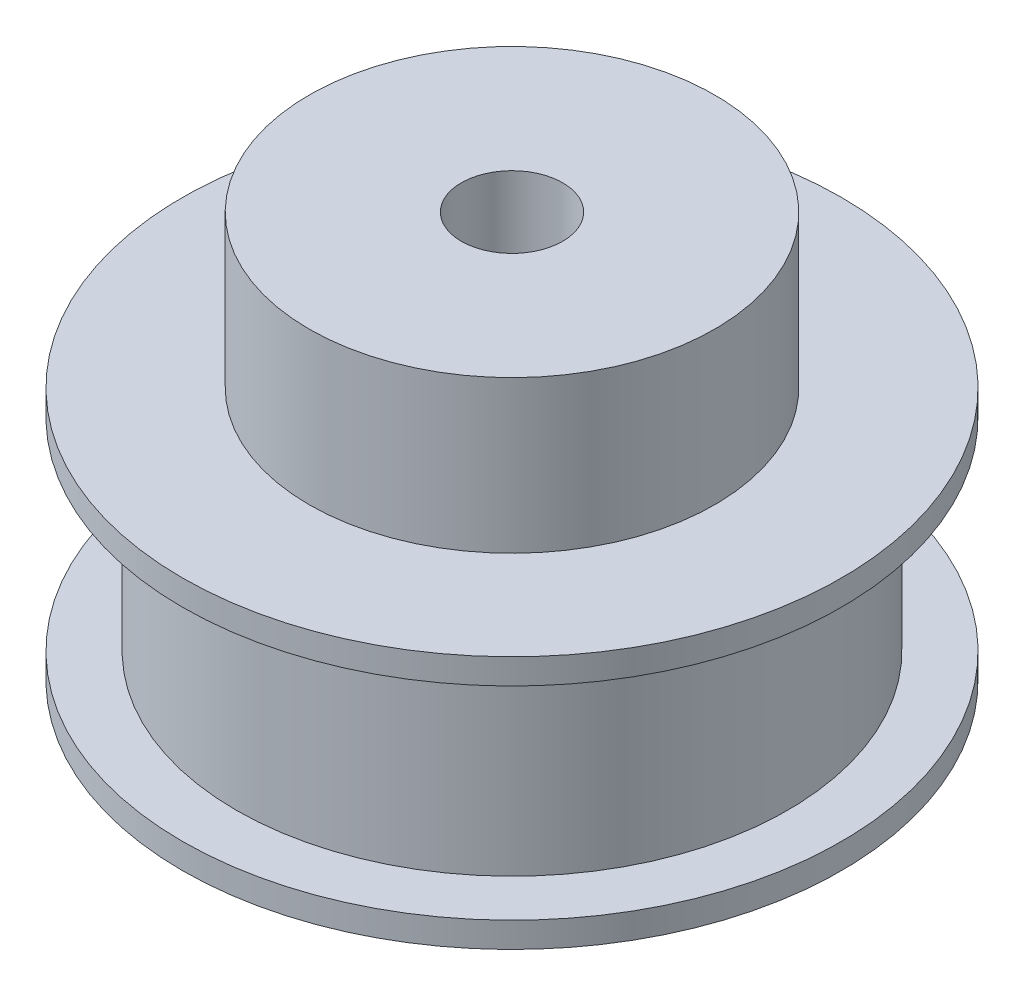
SolidWorks part; units mm, degrees
ref_plane "Plan de face" through (0, 0, 0) normal (0, 0, 1) x (1, 0, 0)
ref_plane "Plan de dessus" through (0, 0, 0) normal (0, 1, 0) x (1, 0, 0)
ref_plane "Plan de droite" through (0, 0, 0) normal (1, 0, 0) x (0, 0, -1)
sketch "Esquisse1" plane through (0, 0, 0) normal (0, 1, 0) x (1, 0, 0)
  circle A0 centre (0, 0) radius 13
extrude "Extrusion1" add sketch "Esquisse1" along normal blind 1
sketch "Esquisse2" plane through (0, 1, 0) normal (0, 1, 0) x (-1, 0, 0)
  circle A0 centre (0, 0) radius 10.875
extrude "Extrusion2" add sketch "Esquisse2" along normal blind 8
sketch "Esquisse3" plane through (0, 9, 0) normal (0, 1, 0) x (-1, 0, 0)
  circle A0 centre (0, 0) radius 13
extrude "Extrusion3" add sketch "Esquisse3" along normal blind 1
sketch "Esquisse4" plane through (0, 10, 0) normal (0, 1, 0) x (-1, 0, 0)
  circle A0 centre (0, 0) radius 8
extrude "Extrusion4" add sketch "Esquisse4" along normal blind 6
sketch "Esquisse5" plane through (0, 16, 0) normal (0, 1, 0) x (-1, 0, 0)
  circle A0 centre (0, 0) radius 2
extrude "Extrusion5" cut sketch "Esquisse5" against normal through all
